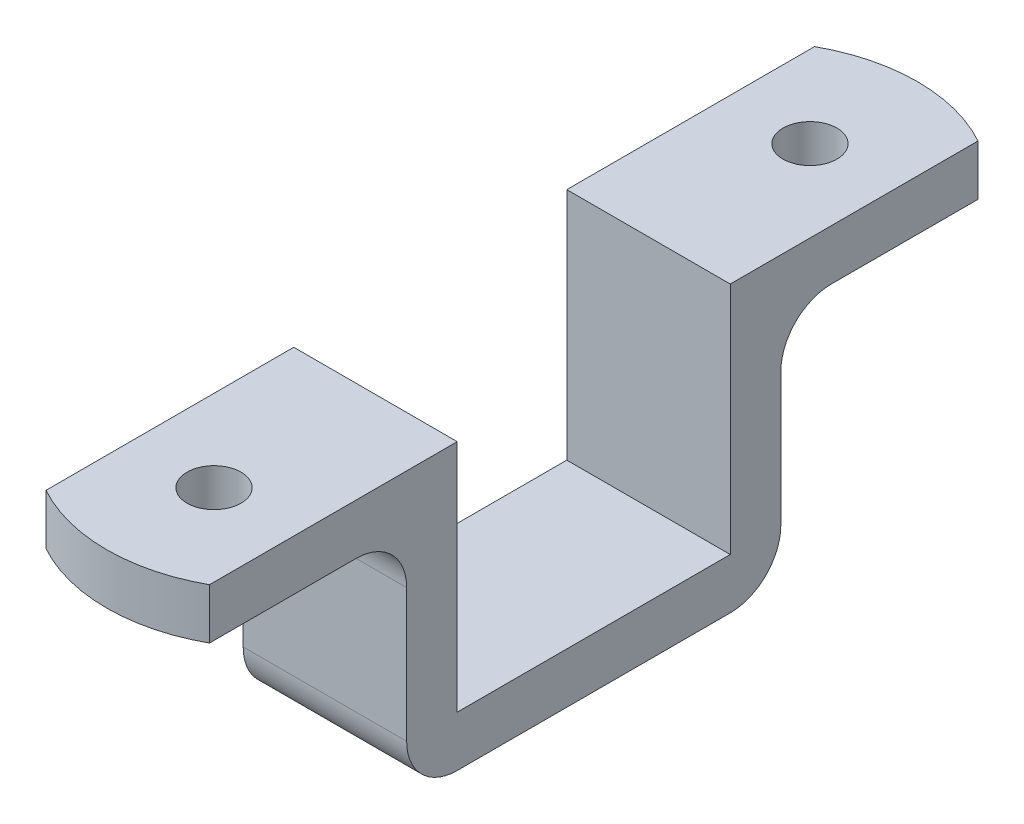
SolidWorks part; units mm, degrees
ref_plane "Front Plane" through (0, 0, 0) normal (0, 0, 1) x (1, 0, 0)
ref_plane "Top Plane" through (0, 0, 0) normal (0, 1, 0) x (1, 0, 0)
ref_plane "Right Plane" through (0, 0, 0) normal (1, 0, 0) x (0, 0, -1)
sketch "Sketch1" plane through (0, 0, 0) normal (1, 0, 0) x (0, 0, -1)
  line L0 (0, 0) -> (-16.9, 0)
  line L1 (-16.9, 0) -> (-16.9, -13.9)
  line L2 (-16.9, -13.9) -> (-33.1, -13.9)
  line L3 (-33.1, -13.9) -> (-33.1, 0)
  line L4 (-33.1, 0) -> (-50, 0)
  line L5 (-50, 0) -> (-50, -3)
  line L6 (-50, -3) -> (-36.1, -3)
  line L7 (-36.1, -3) -> (-36.1, -16.9)
  line L8 (-36.1, -16.9) -> (-13.9, -16.9)
  line L9 (-13.9, -16.9) -> (-13.9, -3)
  line L10 (-13.9, -3) -> (0, -3)
  line L11 (0, -3) -> (0, 0)
  dimension "D1" = 50
  dimension "D2" = 13.9
  dimension "D3" = 16.2
  dimension "D4" = 3
  dimension "D5" = 3
  dimension "D6" = 3
  dimension "D7" = 3
  dimension "D8" = 3
extrude "Boss-Extrude1" add sketch "Sketch1" along normal blind 9.7
fillet "Fillet3" radius 3 4 edges at (4.85, -3, 13.9) (4.85, -16.9, 13.9) (4.85, -16.9, 36.1) (4.85, -3, 36.1)
sketch "Sketch2" plane through (0, -3, 0) normal (0, -1, 0) x (1, 0, 0)
  line L0 (0, 33.1) -> (0, 16.9) construction
  line L1 (9.7, 50) -> (0, 50) construction
  circle A0 centre (4.85, 42.68) radius 1.6
  circle A1 centre (4.85, 7.32) radius 1.6
  point P7 (0, 25)
  point P11 (4.85, 50)
  dimension "D3" = 3.2
  dimension "D1" = 35.36
  dimension "D2" = 17.68
extrude "Cut-Extrude1" cut sketch "Sketch2" against normal blind 9.7
sketch "Sketch3" plane through (0, -3, 0) normal (0, -1, 0) x (1, 0, 0)
  line L0 (0, 0) -> (9.7, 0)
  line L1 (9.7, 0) -> (9.7, 2.2)
  line L2 (9.7, 10.9) -> (9.7, 0) construction
  line L3 (0, 0) -> (0, 2.2)
  line L4 (0, 10.9) -> (0, 0) construction
  line L5 (0, 47.8) -> (0, 50)
  line L6 (0, 50) -> (0, 39.1) construction
  line L7 (0, 50) -> (9.7, 50)
  line L8 (9.7, 50) -> (9.7, 47.8)
  line L9 (9.7, 50) -> (9.7, 39.1) construction
  arc A0 (9.7, 2.2) -> (0, 2.2) centre (4.85, 10.9451) cw
  arc A1 (0, 47.8) -> (9.7, 47.8) centre (4.85, 39.0549) cw
  dimension "D1" = 10
  dimension "D3" = 10
  dimension "D2" = 2.2
  dimension "D4" = 2.2
extrude "Cut-Extrude2" cut sketch "Sketch3" against normal blind 9.7
